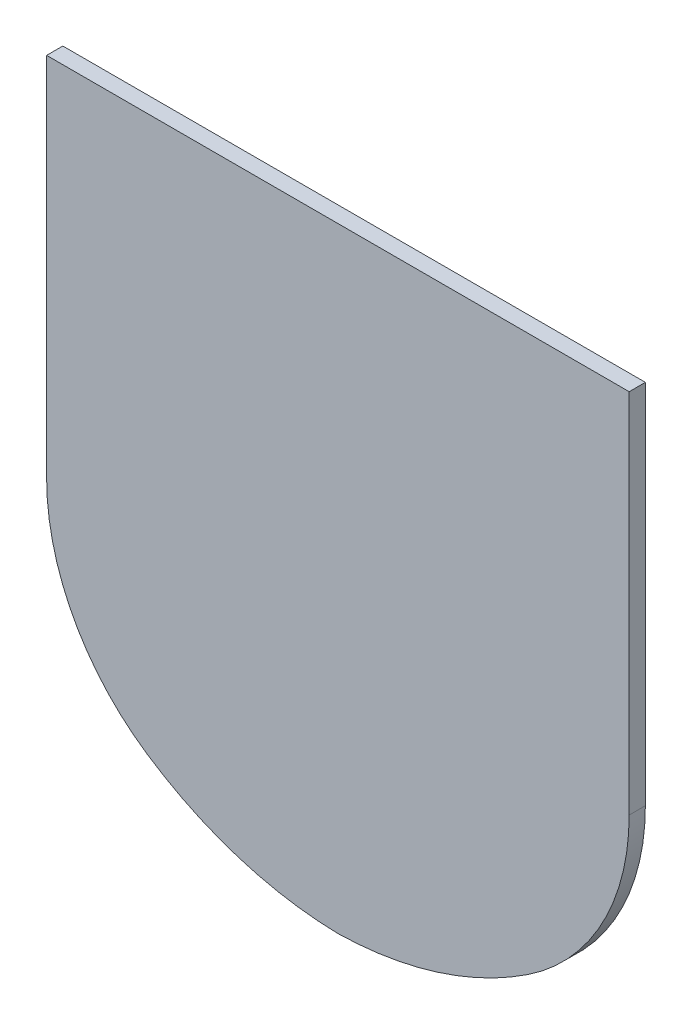
SolidWorks part; units mm, degrees
ref_plane "前基準面" through (0, 0, 0) normal (0, 0, 1) x (1, 0, 0)
ref_plane "上基準面" through (0, 0, 0) normal (0, 1, 0) x (1, 0, 0)
ref_plane "右基準面" through (0, 0, 0) normal (1, 0, 0) x (0, 0, -1)
sketch "草圖1" plane through (0, 0, 0) normal (0, 0, 1) x (1, 0, 0)
  line L0 (0, 52.2154) -> (0, 33.2154)
  line L2 (-9, 52.2154) -> (9, 52.2154)
  line L3 (-9, 52.2154) -> (-9, 33.2154)
  line L4 (-9, 33.2154) -> (9, 33.2154)
  line L5 (9, 52.2154) -> (9, 33.2154)
  line L6 (-9, 52.2154) -> (9, 33.2154) construction
  line L7 (-9, 33.2154) -> (9, 52.2154) construction
  point P3 (0, 42.7154)
  dimension "D1" = 18
  dimension "D2" = 19
extrude "填料-伸長2" add sketch "草圖1" along normal blind 0.5 contours L5 L2 L0 L4 | L3 L4 L0 L2
sketch "草圖3" plane through (0, 0, 0.5) normal (0, 0, 1) x (1, 0, 0)
  line L0 (-9, 52.2154) -> (-9, 38.2154) construction
  line L1 (-9, 52.2154) -> (-9, 33.2154) construction
  line L2 (-9, 33.2154) -> (9, 33.2154) construction
  line L3 (0, 33.2154) -> (0, 52.2154) construction
  line L4 (-9, 52.2154) -> (9, 52.2154) construction
  line L5 (9, 33.2154) -> (-9, 33.2154)
  line L6 (-9, 33.2154) -> (-9, 38.2154)
  line L7 (9, 33.2154) -> (9, 38.2154)
  arc A0 (-9, 38.2154) -> (0, 33.2154) centre (0.221, 44.2132) ccw
  arc A1 (9, 38.2154) -> (0, 33.2154) centre (-0.221, 44.2132) cw
  line M6 (9, 33.2154) -> (9, 52.2154)
  line M8 (-9, 52.2154) -> (-9, 33.2154)
  line M9 (-9, 33.2154) -> (9, 33.2154)
  dimension "D2" = 11
  dimension "D1" = 14
extrude "除料-伸長1" cut sketch "草圖3" against normal through all contours A1 L5 M6 | A0 M8 M9
fillet "圓角1" radius 7 2 edges at (-9, 38.2154, 0.25) (9, 38.2154, 0.25)
